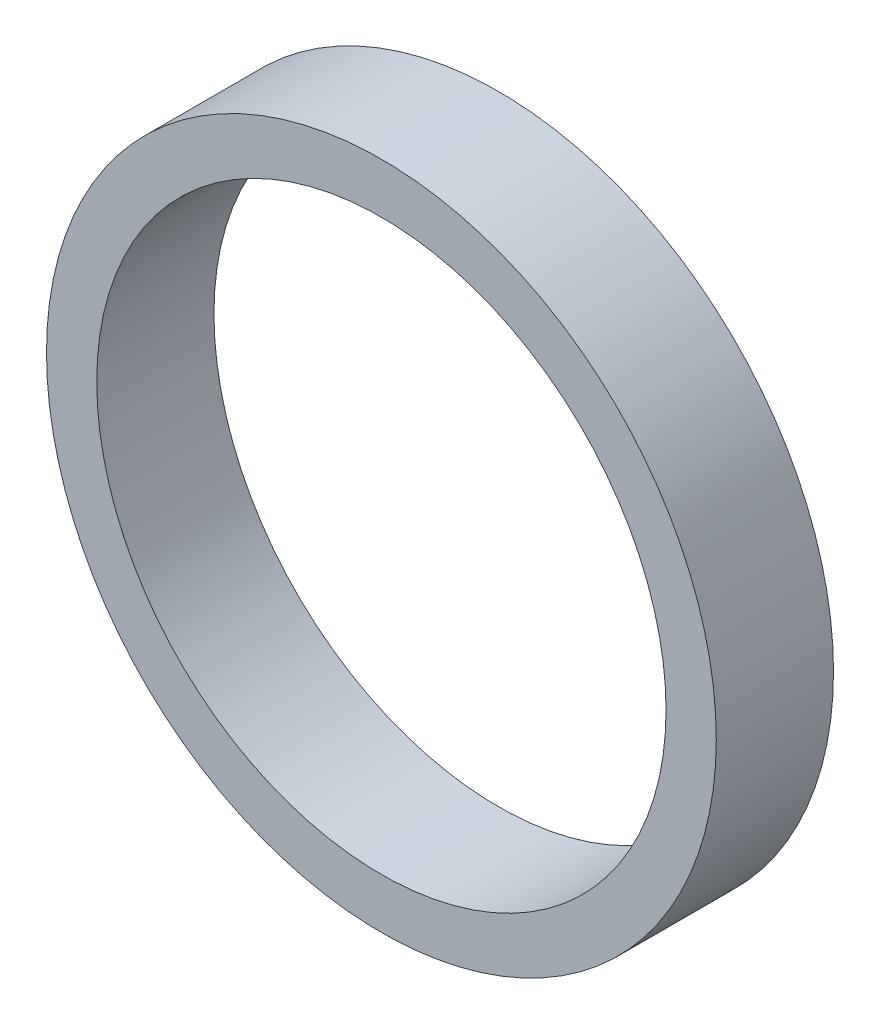
SolidWorks part; units mm, degrees
ref_plane "Front Plane" through (0, 0, 0) normal (0, 0, 1) x (1, 0, 0)
ref_plane "Top Plane" through (0, 0, 0) normal (0, 1, 0) x (1, 0, 0)
ref_plane "Right Plane" through (0, 0, 0) normal (1, 0, 0) x (0, 0, -1)
sketch "Sketch1" plane through (0, 0, 0) normal (0, 0, 1) x (1, 0, 0)
  circle A0 centre (0, 0) radius 20
  circle A1 centre (0, 0) radius 17
  dimension "D1" = 34
  dimension "D2" = 40
extrude "Boss-Extrude1" add sketch "Sketch1" along normal blind 7
